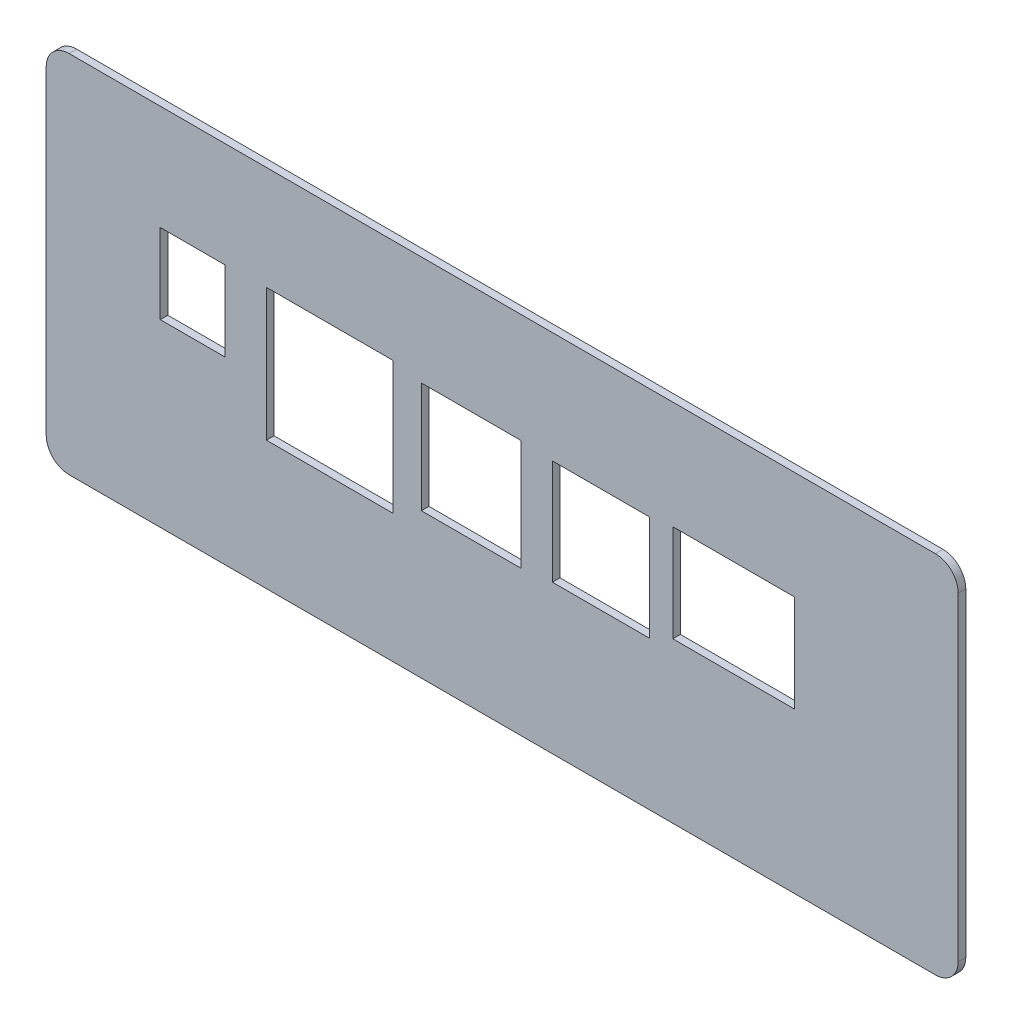
SolidWorks part; units mm, degrees
ref_plane "Front Plane" through (0, 0, 0) normal (0, 0, 1) x (1, 0, 0)
ref_plane "Top Plane" through (0, 0, 0) normal (0, 1, 0) x (1, 0, 0)
ref_plane "Right Plane" through (0, 0, 0) normal (1, 0, 0) x (0, 0, -1)
sketch "Sketch1" plane through (0, 0, 0) normal (0, 0, 1) x (1, 0, 0)
  line L22 (-51.9401, -23.8056) -> (62.0599, -23.8056)
  line L23 (65.0599, -20.8056) -> (65.0599, 0.1944)
  line L29 (-54.9401, 0.1944) -> (-54.9401, -20.8056)
  line L30 (65.0599, 0.1944) -> (65.0599, 21.1944)
  line L31 (62.0599, 24.1944) -> (-51.9401, 24.1944)
  line L32 (-54.9401, 21.1944) -> (-54.9401, 0.1944)
  line L46 (-5.5823, -4.7287) -> (7.5191, -4.7287)
  line L47 (7.5191, -4.7287) -> (7.5191, 9.8295)
  line L48 (7.5191, 9.8295) -> (-5.5823, 9.8295)
  line L49 (-5.5823, 9.8295) -> (-5.5823, -4.7287)
  line L54 (-39.9401, 10.3694) -> (-39.9401, -0.1306)
  line L55 (-31.4401, 10.3694) -> (-39.9401, 10.3694)
  line L56 (-31.4401, -0.1306) -> (-31.4401, 10.3694)
  line L57 (-39.9401, -0.1306) -> (-31.4401, -0.1306)
  line L62 (-25.969, -6.8851) -> (-9.2901, -6.8851)
  line L63 (-9.2901, -6.8851) -> (-9.2901, 10.5332)
  line L64 (-9.2901, 10.5332) -> (-25.969, 10.5332)
  line L65 (-25.969, 10.5332) -> (-25.969, -6.8851)
  line L70 (27.5099, -2.7806) -> (43.5051, -2.7806)
  line L71 (43.5051, -2.7806) -> (43.5051, 9.9932)
  line L72 (43.5051, 9.9932) -> (27.5099, 9.9932)
  line L73 (27.5099, 9.9932) -> (27.5099, -2.7806)
  line L78 (24.4599, 9.5694) -> (11.6599, 9.5694)
  line L79 (11.6599, 9.5694) -> (11.6599, -4.2506)
  line L80 (11.6599, -4.2506) -> (24.4599, -4.2506)
  line L81 (24.4599, -4.2506) -> (24.4599, 9.5694)
  arc A8 (62.0599, -23.8056) -> (65.0599, -20.8056) centre (62.0599, -20.8056) ccw
  arc A11 (-54.9401, -20.8056) -> (-51.9401, -23.8056) centre (-51.9401, -20.8056) ccw
  arc A12 (65.0599, 21.1944) -> (62.0599, 24.1944) centre (62.0599, 21.1944) ccw
  arc A13 (-51.9401, 24.1944) -> (-54.9401, 21.1944) centre (-51.9401, 21.1944) ccw
extrude "Boss-Extrude1" add sketch "Sketch1" along normal blind 1
